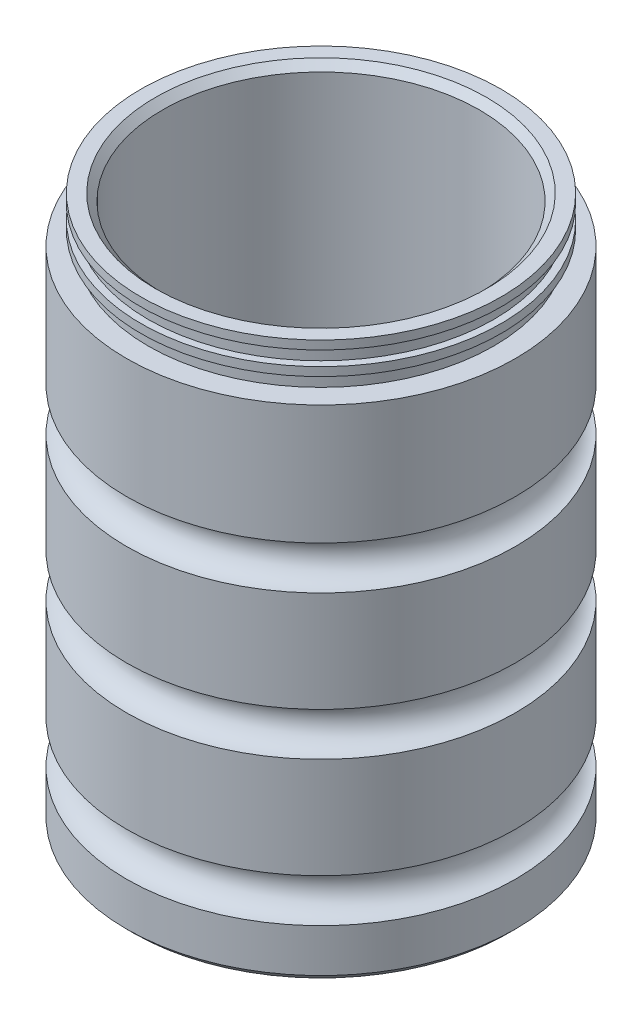
SolidWorks part; units mm, degrees
material "AISI 316 Barre d'acier inoxydable recuit (SS)"
ref_plane "Plan de face" through (0, 0, 0) normal (0, 0, 1) x (1, 0, 0)
ref_plane "Plan de dessus" through (0, 0, 0) normal (0, 1, 0) x (1, 0, 0)
ref_plane "Plan de droite" through (0, 0, 0) normal (1, 0, 0) x (0, 0, -1)
sketch "Esquisse1" plane through (0, 0, 0) normal (0, 0, 1) x (1, 0, 0)
  line L0 (0, -29.1154) -> (0, 30.7029) construction
  line L4 (-2, 24) -> (-2, 3) construction
  line L5 (-2, 3) -> (0, 3) construction
  line L9 (0, 0) -> (-13.5, 0)
  line L10 (-13.5, 0) -> (-13.5, 34.8) construction
  line L11 (-2, 24) -> (-11, 33) construction
  line L13 (-12.5, 31.7574) -> (-12.5, 38) construction
  line L14 (-12.5, 38) -> (-11, 38)
  line L17 (-11, 38) -> (-11, 33)
  line L18 (-12.5, 38) -> (-12.5, 37.4)
  line L19 (-12.5, 37.4) -> (-12, 37.4)
  line L20 (-12, 37.4) -> (-12, 36.4)
  line L21 (-12, 36.4) -> (-12.5, 36.4)
  line L22 (-12.5, 36.4) -> (-12.5, 35.8)
  line L23 (-12.5, 35.8) -> (-12, 35.8)
  line L24 (-12, 35.8) -> (-12, 34.8)
  line L29 (-12, 34.8) -> (-12.5, 34.8)
  line L33 (-13.5, 34.8) -> (-12.5, 34.8)
  line L34 (0, 3) -> (0, 0)
  line L35 (-13.5, 34.8) -> (-13.5, 26.5)
  line L36 (-13.5, 23.5) -> (-13.5, 16.5)
  line L37 (-13.5, 13.5) -> (-13.5, 6.5)
  line L38 (-13.5, 3.5) -> (-13.5, 0)
  line L39 (-2, 24) -> (-2, 8) construction
  line L40 (-2, 8) -> (0, 12) construction
  line L41 (0, 12) -> (0, 3)
  line L42 (-11, 33) -> (-11, 12)
  line L43 (-11, 12) -> (0, 12)
  arc A0 (-13.5, 26.5) -> (-13.5, 23.5) centre (-13.5, 25) cw
  arc A1 (-13.5, 16.5) -> (-13.5, 13.5) centre (-13.5, 15) cw
  arc A2 (-13.5, 6.5) -> (-13.5, 3.5) centre (-13.5, 5) cw
  dimension "D5" = 1.5
  dimension "D1" = 2
  dimension "D2" = 13.5
  dimension "D3" = 11
  dimension "D6" = 3
  dimension "D7" = 10
  dimension "D8" = 5
  dimension "D9" = 11
  dimension "D10" = 1.5
  dimension "45" = 45
  dimension "D11" = 5
  dimension "D13" = 21
  dimension "D14" = 1
  dimension "D15" = 0.5
  dimension "D16" = 9
  dimension "D17" = 0.6
  dimension "38" = 38
revolve "Révolution1" add sketch "Esquisse1" angle 360 about L0
sketch "Esquisse2" plane through (0, 0, 0) normal (0, -1, 0) x (1, 0, 0)
  line L0 (0, 0) -> (13.5, 0) construction
  circle A1 centre (8, 0) radius 2.5
  circle A2 centre (-8, 0) radius 2.5
  circle A5 centre (0, 0) radius 13.5 construction
  point P3 (-7.852, -4.3985)
  point P5 (0, 0)
  point P8 (0, 0)
  point P14 (0, 0)
  dimension "D1" = 5
  dimension "D2" = 8
  dimension "D3" = 2
extrude "Enlèv. mat.-Extru.1" cut sketch "Esquisse2" against normal blind 10
sketch "Esquisse4" plane through (0, 0, 0) normal (0, -1, 0) x (1, 0, 0)
  circle A0 centre (0, 0) radius 2
  dimension "D1" = 4
extrude "Enlèv. mat.-Extru.3" cut sketch "Esquisse4" against normal through all
chamfer "Chanfrein4" distance 0.5 angle 45 2 edges at (0, 12, -2) (0, 0, -2)
chamfer "Chanfrein2" distance 0.5 angle 45 2 edges at (-8, 0, -2.5) (8, 0, -2.5)
chamfer "Chanfrein3" distance 0.5 angle 45 2 edges at (0, 0, -13.5) (0, 38, -11)
equation "\"1à.00mm\"=12"
